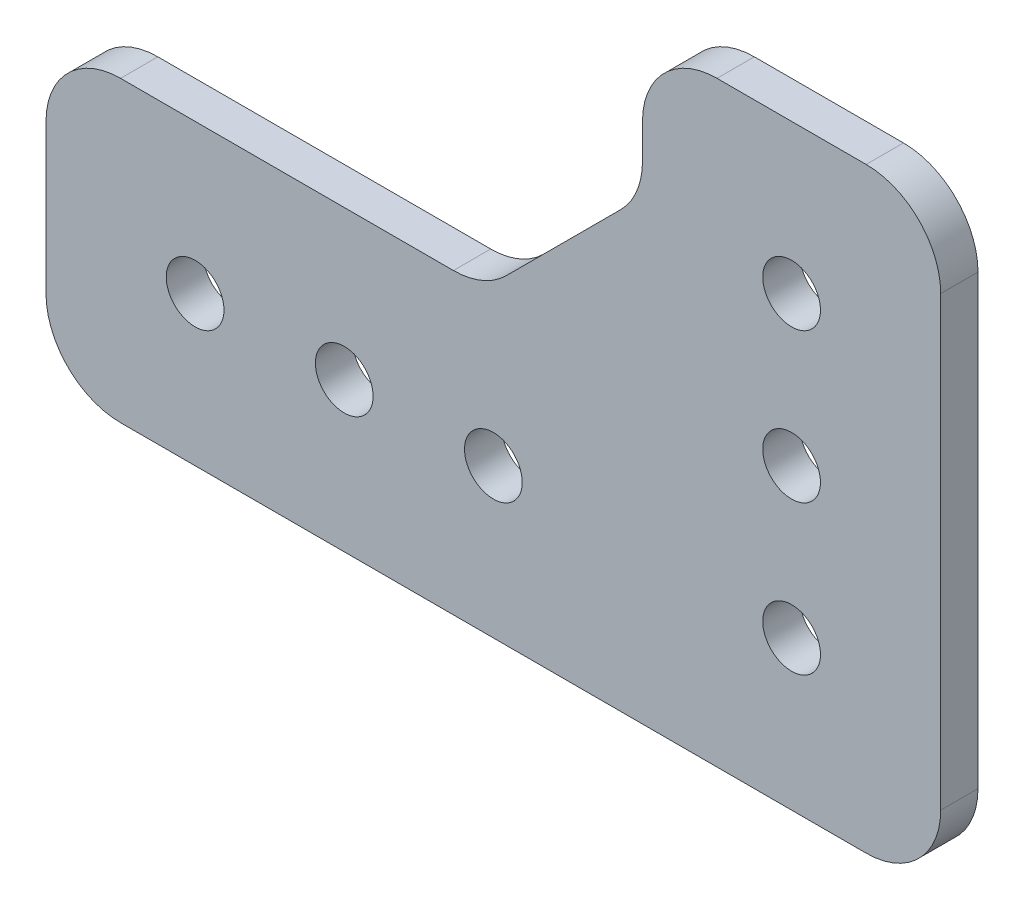
SolidWorks part; units mm, degrees
ref_plane "Front Plane" through (0, 0, 0) normal (0, 0, 1) x (1, 0, 0)
ref_plane "Top Plane" through (0, 0, 0) normal (0, 1, 0) x (1, 0, 0)
ref_plane "Right Plane" through (0, 0, 0) normal (1, 0, 0) x (0, 0, -1)
sketch "Sketch1" plane through (0, 0, 0) normal (0, 0, 1) x (1, 0, 0)
  line L0 (0, 0) -> (0, 50.8)
  line L1 (0, 50.8) -> (-25.4, 50.8)
  line L2 (-25.4, 50.8) -> (-25.4, 38.8704)
  line L3 (-38.8704, 25.4) -> (-76.2, 25.4)
  line L4 (-76.2, 25.4) -> (-76.2, 0)
  line L5 (-76.2, 0) -> (0, 0)
  line L6 (-25.4, 38.8704) -> (-38.8704, 25.4)
  dimension "D1" = 25.4
  dimension "D2" = 25.4
  dimension "D3" = 76.2
  dimension "D4" = 45
  dimension "D5" = 50.8
  dimension "D6" = 19.05
extrude "Boss-Extrude1" add sketch "Sketch1" along normal blind 3.175
fillet "Fillet1" radius 6.35 7 edges at (-76.2, 25.4, 1.5875) (-76.2, 0, 1.5875) (0, 0, 1.5875) (0, 50.8, 1.5875) (-25.4, 50.8, 1.5875) (-38.8704, 25.4, 1.5875) (-25.4, 38.8704, 1.5875)
hole_wizard "#10 (0.1935) Diameter Hole1" positions "Sketch2" profile "Sketch4" hole size "#10" standard "ANSI Inch" end condition up to next
sketch "Sketch2" plane through (0, 0, 3.175) normal (0, 0, 1) x (1, 0, 0)
  line L0 (-76.2, 19.05) -> (-76.2, 6.35) construction
  line L1 (-6.35, 50.8) -> (-19.05, 50.8) construction
  line L2 (0, 6.35) -> (0, 44.45) construction
  line L3 (-41.5006, 25.4) -> (-69.85, 25.4) construction
  point P0 (-63.5, 12.7)
  point P2 (-50.8, 12.7)
  point P4 (-12.7, 25.4)
  point P6 (-12.7, 38.1)
  point P13 (-38.1, 12.7)
  point P19 (-12.7, 12.7)
  dimension "D1" = 12.7
  dimension "D2" = 12.7
  dimension "D3" = 12.7
  dimension "D4" = 12.7
  dimension "D5" = 12.7
  dimension "D6" = 12.7
  dimension "D7" = 12.7
  dimension "D8" = 12.7
sketch "Sketch4" plane through (-63.5, 12.7, 3.175) normal (1, 0, 0) x (0, -1, 0)
  line L0 (0, 0) -> (0, 3.175)
  line L1 (0, 3.175) -> (2.4574, 3.175)
  line L2 (2.4574, 3.175) -> (2.4574, 0)
  line L5 (2.4574, 0) -> (0, 0)
  line L11 (0, -6.35) -> (0, 107.95) construction
  dimension "Thru Hole Dia." = 4.9149
  dimension "Thru Hole Depth" = 3.175
